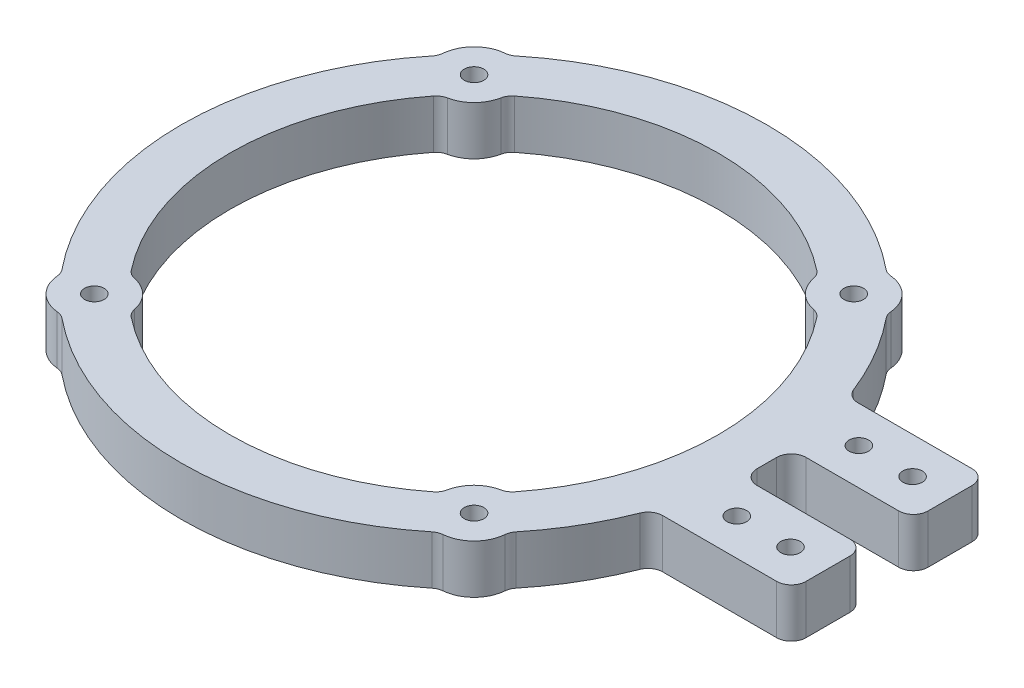
SolidWorks part; units mm, degrees
material "6063-T83"
ref_plane "Front Plane" through (0, 0, 0) normal (0, 0, 1) x (1, 0, 0)
ref_plane "Top Plane" through (0, 0, 0) normal (0, 1, 0) x (1, 0, 0)
ref_plane "Right Plane" through (0, 0, 0) normal (1, 0, 0) x (0, 0, -1)
sketch "Sketch1" plane through (0, 0, 0) normal (0, 1, 0) x (1, 0, 0)
  line L0 (0, -50) -> (0, -60) construction
  line L1 (0, 0) -> (0, -50) construction
  line L2 (56.5685, -20) -> (85, -20)
  line L3 (85, -20) -> (85, -5)
  line L4 (85, -5) -> (60, -5)
  line L5 (60, -5) -> (60, 5)
  line L6 (60, 5) -> (85, 5)
  line L7 (85, 5) -> (85, 20)
  line L8 (85, 20) -> (56.5685, 20)
  circle A0 centre (0, 0) radius 50
  circle A1 centre (0, 0) radius 60 construction
  arc A2 (56.5685, 20) -> (56.5685, -20) centre (0, 0) ccw
  dimension "D1" = 100
  dimension "D2" = 10
  dimension "D3" = 10
  dimension "D4" = 15
  dimension "D6" = 25
extrude "Boss-Extrude1" add sketch "Sketch1" along normal blind 10
sketch "Sketch3" plane through (0, 10, 0) normal (0, 1, 0) x (1, 0, 0)
  line L0 (38.8909, 38.8909) -> (38.8909, -38.8909) construction
  line L1 (60, -5) -> (60, 5) construction
  circle A0 centre (0, 0) radius 55 construction
  circle A1 centre (38.8909, -38.8909) radius 7
  circle A2 centre (-38.8909, -38.8909) radius 7
  circle A3 centre (-38.8909, 38.8909) radius 7
  circle A4 centre (38.8909, 38.8909) radius 7
  point P14 (0, 0)
  dimension "D1" = 110
  dimension "D2" = 14
  dimension "D3" = 4
extrude "Boss-Extrude2" add sketch "Sketch3" against normal up to surface (10 mm away) up to face at (57.0711, 0, 0)
sketch "Sketch4" plane through (0, 10, 0) normal (0, 1, 0) x (1, 0, 0)
  circle A0 centre (38.8909, -38.8909) radius 2
  circle A1 centre (-38.8909, -38.8909) radius 2
  circle A2 centre (-38.8909, 38.8909) radius 2
  circle A3 centre (38.8909, 38.8909) radius 2
  point P12 (0, 0)
  dimension "D1" = 4
  dimension "D2" = 4
extrude "Cut-Extrude1" cut sketch "Sketch4" against normal blind 10
fillet "Fillet1" radius 3 24 edges at (85, 5, -20) (85, 5, -5) (85, 5, 5) (85, 5, 20) (31.9018, 5, 38.5003) (38.5003, 5, 31.9018) (38.5003, 5, -31.9018) (31.9018, 5, -38.5003) (-31.9018, 5, -38.5003) (-38.5003, 5, -31.9018) (-38.6573, 5, -45.887) (-45.887, 5, -38.6573) (45.887, 5, -38.6573) (38.6573, 5, -45.887) (-38.5003, 5, 31.9018) (-31.9018, 5, 38.5003) (-45.887, 5, 38.6573) (-38.6573, 5, 45.887) (38.6573, 5, 45.887) (45.887, 5, 38.6573) (56.5685, 5, 20) (56.5685, 5, -20) (60, 5, 5) (60, 5, -5)
sketch "Sketch5" plane through (0, 10, 0) normal (0, 1, 0) x (1, 0, 0)
  line L0 (58.6515, 20) -> (85, 5) construction
  line L1 (85, 20) -> (58.6515, 5) construction
  line L2 (58.6515, 5) -> (85, 5) construction
  line L3 (58.6515, 20) -> (58.6515, 5) construction
  line L4 (66.3258, 12.5) -> (77.3258, 12.5) construction
  line L5 (58.6515, 20) -> (85, 20) construction
  line L6 (85, 20) -> (85, 5) construction
  line L7 (63, 5) -> (82, 5) construction
  line L8 (85, 8) -> (85, 17) construction
  line L9 (58.6515, -5) -> (85, -20) construction
  line L10 (85, -5) -> (58.6515, -20) construction
  line L11 (58.6515, -20) -> (85, -20) construction
  line L12 (58.6515, -5) -> (58.6515, -20) construction
  line L13 (66.3258, -12.5) -> (77.3258, -12.5) construction
  line L14 (58.6515, -5) -> (85, -5) construction
  line L15 (85, -5) -> (85, -20) construction
  line L16 (82, -5) -> (63, -5) construction
  line L17 (58.6515, -20) -> (82, -20) construction
  circle A0 centre (66.3258, 12.5) radius 2
  circle A1 centre (77.3258, 12.5) radius 2
  circle A2 centre (66.3258, -12.5) radius 2
  circle A3 centre (77.3258, -12.5) radius 2
  point P11 (71.8258, 12.5)
  point P21 (71.8258, -12.5)
  point P27 (66.8258, -12.5)
  dimension "D2" = 4
  dimension "D3" = 4
  dimension "D5" = 4
  dimension "D6" = 4
  dimension "D1" = 11
  dimension "D4" = 11
extrude "Cut-Extrude2" cut sketch "Sketch5" against normal blind 10
